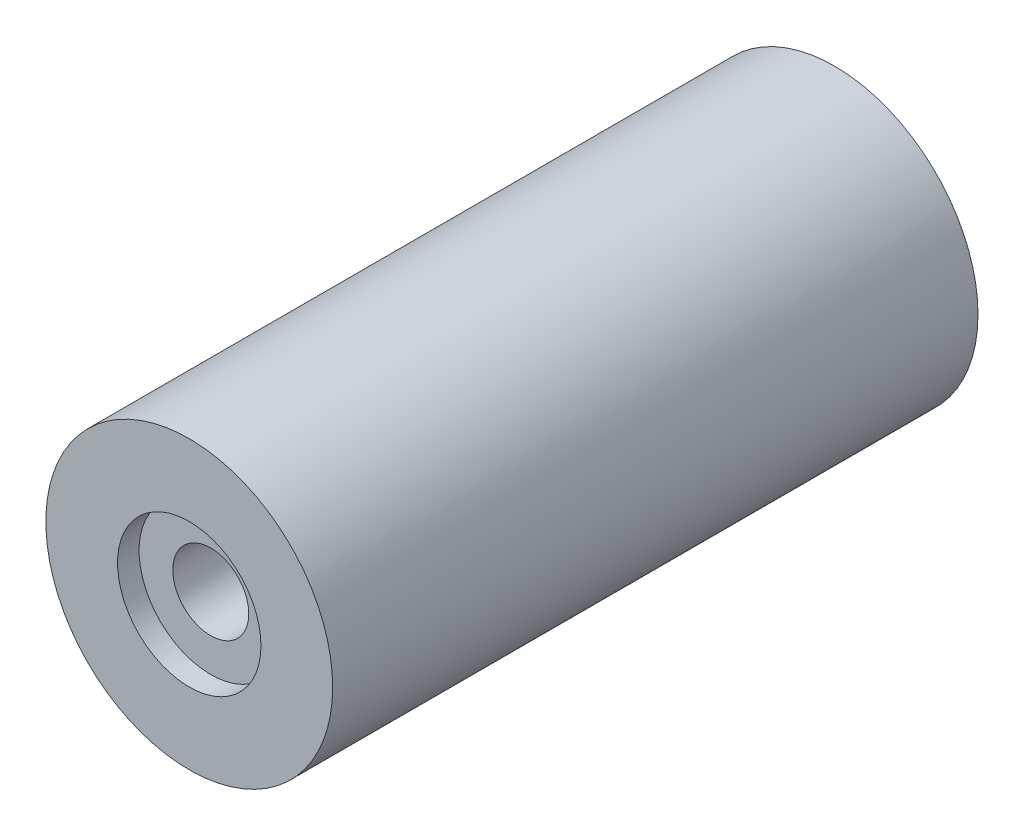
SolidWorks part; units mm, degrees
ref_plane "Front Plane" through (0, 0, 0) normal (0, 0, 1) x (1, 0, 0)
ref_plane "Top Plane" through (0, 0, 0) normal (0, 1, 0) x (1, 0, 0)
ref_plane "Right Plane" through (0, 0, 0) normal (1, 0, 0) x (0, 0, -1)
sketch "Sketch1" plane through (0, 0, 0) normal (0, 0, 1) x (1, 0, 0)
  circle A0 centre (0, 0) radius 10
  dimension "D1" = 20
extrude "Boss-Extrude1" add sketch "Sketch1" against normal blind 45
sketch "Sketch2" plane through (0, 0, 0) normal (0, 0, 1) x (1, 0, 0)
  circle A0 centre (0, 0) radius 2.65
  dimension "D1" = 5.3
extrude "Cut-Extrude1" cut sketch "Sketch2" against normal through all
sketch "Sketch3" plane through (0, 0, 0) normal (0, 0, 1) x (1, 0, 0)
  circle A0 centre (0, 0) radius 5
  dimension "D1" = 10
extrude "Cut-Extrude2" cut sketch "Sketch3" against normal blind 1.5
